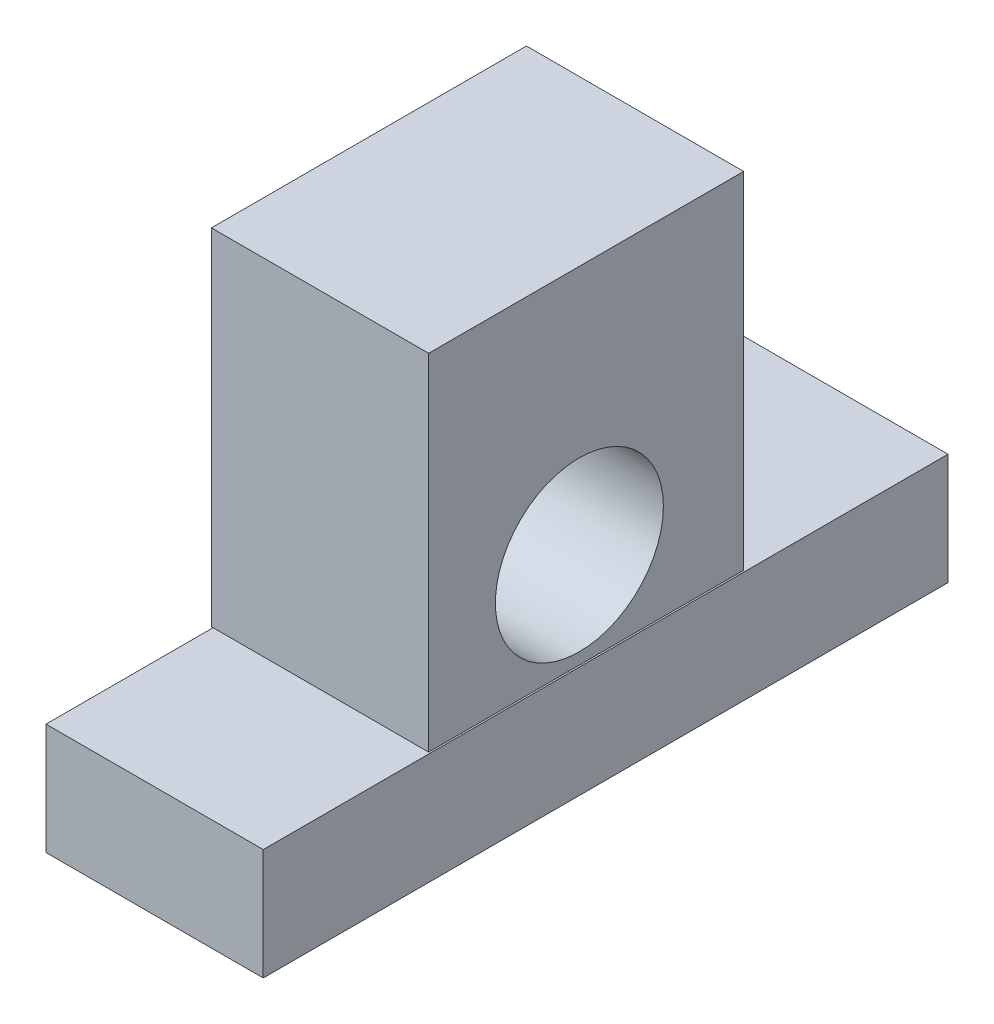
SolidWorks part; units mm, degrees
ref_plane "Front Plane" through (0, 0, 0) normal (0, 0, 1) x (1, 0, 0)
ref_plane "Top Plane" through (0, 0, 0) normal (0, 1, 0) x (1, 0, 0)
ref_plane "Right Plane" through (0, 0, 0) normal (1, 0, 0) x (0, 0, -1)
sketch "Sketch1" plane through (0, 0, 0) normal (1, 0, 0) x (0, 0, -1)
  line L1 (-22.0275, 36.5125) -> (24.01, 36.5125)
  line L2 (-22.0275, 36.5125) -> (-22.0275, -13.97)
  line L3 (-22.0275, -13.97) -> (24.01, -13.97)
  line L4 (24.01, 36.5125) -> (24.01, -13.97)
  circle A0 centre (0, 0) radius 12.2773
  dimension "D1" = 13.97
  dimension "D2" = 36.5125
extrude "Boss-Extrude1" add sketch "Sketch1" along normal blind 31.75
ref_plane "Plane1" through (0, -13.97, 0) normal (0, -1, 0) x (-1, 0, 0)
sketch "Sketch3" plane through (0, -13.97, 0) normal (0, -1, 0) x (-1, 0, 0)
  line L1 (-0.2427, 53.63) -> (-31.9927, 53.63)
  line L2 (-0.2427, 53.63) -> (-0.2427, -46.446)
  line L3 (-0.2427, -46.446) -> (-31.9927, -46.446)
  line L4 (-31.9927, 53.63) -> (-31.9927, -46.446)
  dimension "D1" = 31.75
  dimension "D2" = 100.076
extrude "Boss-Extrude3" add sketch "Sketch3" along normal blind 16.256
